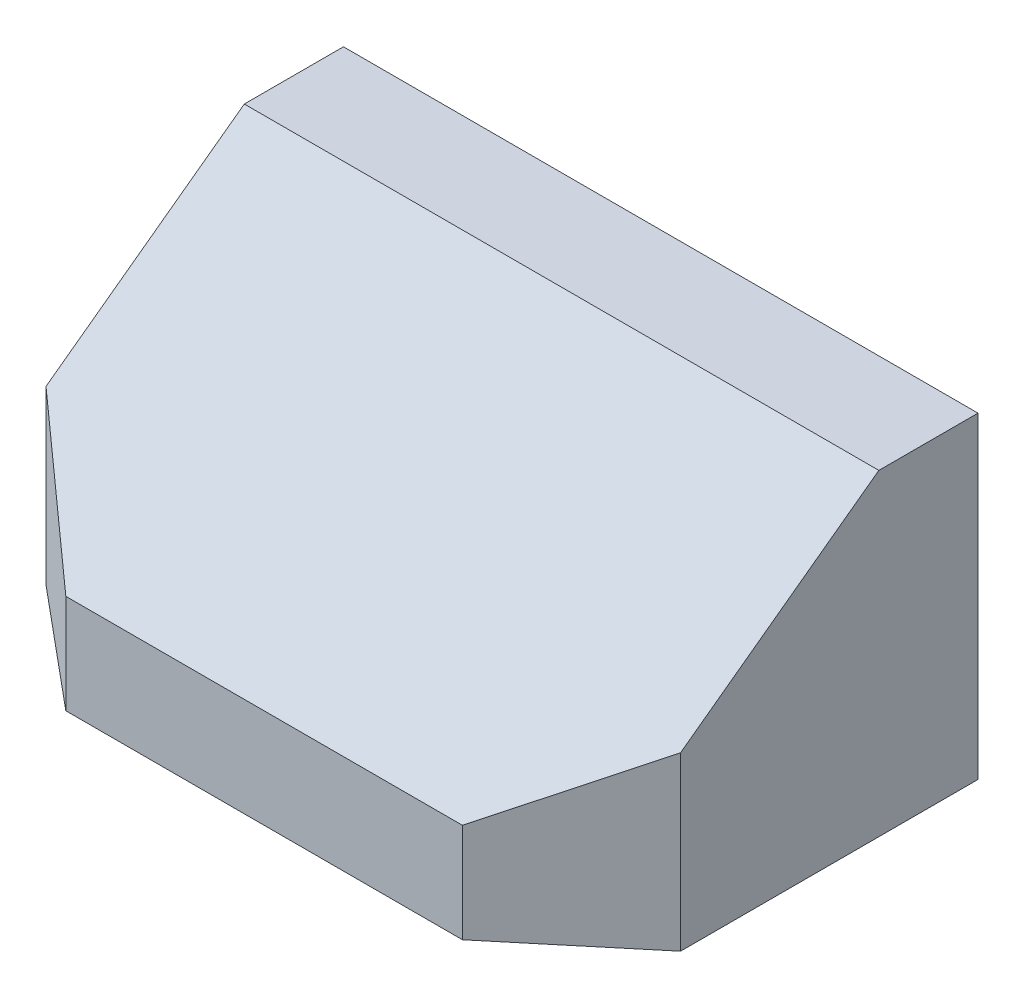
SolidWorks part; units mm, degrees
ref_plane "Front Plane" through (0, 0, 0) normal (0, 0, 1) x (1, 0, 0)
ref_plane "Top Plane" through (0, 0, 0) normal (0, 1, 0) x (1, 0, 0)
ref_plane "Right Plane" through (0, 0, 0) normal (1, 0, 0) x (0, 0, -1)
sketch "Sketch1" plane through (0, 0, 0) normal (1, 0, 0) x (0, 0, -1)
  line L0 (0, 0) -> (63.5, 0)
  line L1 (63.5, 0) -> (63.5, 50.8)
  line L2 (63.5, 50.8) -> (47.625, 50.8)
  line L3 (47.625, 50.8) -> (0, 15.875)
  line L4 (0, 15.875) -> (0, 0)
  dimension "D1" = 63.5
  dimension "D2" = 50.8
  dimension "D3" = 15.875
  dimension "D4" = 47.625
  dimension "D5" = 15.875
extrude "Boss-Extrude1" add sketch "Sketch1" against normal blind 101.6
sketch "Sketch3" plane through (0, 0, 0) normal (0, -1, 0) x (1, 0, 0)
  line L0 (0, 0) -> (-19.05, 0)
  line L1 (-101.6, 0) -> (0, 0) construction
  line L2 (-19.05, 0) -> (0, -15.875)
  line L3 (0, 0) -> (0, -63.5) construction
  line L4 (0, -15.875) -> (0, 0)
  dimension "D1" = 15.875
  dimension "D2" = 19.05
extrude "Cut-Extrude1" cut sketch "Sketch3" against normal blind 101.6
sketch "Sketch4" plane through (0, 0, 0) normal (0, -1, 0) x (1, 0, 0)
  line L0 (-101.6, 0) -> (-82.55, 0)
  line L1 (-101.6, 0) -> (-19.05, 0) construction
  line L2 (-82.55, 0) -> (-101.6, -15.875)
  line L3 (-101.6, 0) -> (-101.6, -63.5) construction
  line L4 (-101.6, -15.875) -> (-101.6, 0)
  dimension "D1" = 19.05
  dimension "D2" = 15.875
extrude "Cut-Extrude2" cut sketch "Sketch4" against normal blind 101.6
sketch "Sketch5" plane through (0, 0, -63.5) normal (0, 0, -1) x (-1, 0, 0)
  line L0 (50.8, 50.8) -> (50.8, 0) construction
  line L2 (101.6, 50.8) -> (0, 50.8) construction
  line L3 (101.6, 0) -> (0, 0) construction
  line L4 (76.2, 50.8) -> (25.4, 50.8)
  line L5 (25.4, 50.8) -> (25.4, 31.75)
  line L6 (25.4, 31.75) -> (76.2, 31.75)
  line L9 (76.2, 50.8) -> (76.2, 31.75)
  point P10 (50.8, 31.75)
  dimension "D1" = 19.05
  dimension "D2" = 25.4
